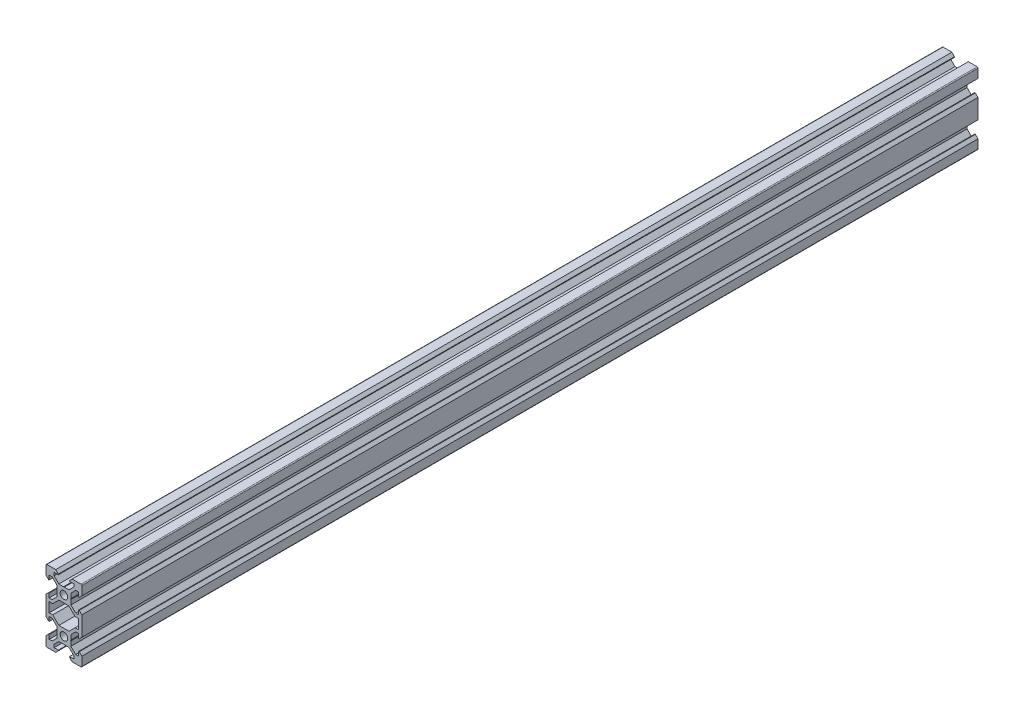
SolidWorks part; units mm, degrees
ref_plane "Front Plane" through (0, 0, 0) normal (0, 0, 1) x (1, 0, 0)
ref_plane "Top Plane" through (0, 0, 0) normal (0, 1, 0) x (1, 0, 0)
ref_plane "Right Plane" through (0, 0, 0) normal (1, 0, 0) x (0, 0, -1)
sketch "Sketch2" plane through (0, 0, 0) normal (0, 0, 1) x (1, 0, 0)
  line L106 (-6.1325, -2.3442) -> (-2.7325, -5.7442)
  line L107 (-8.0932, -2.3442) -> (-6.1325, -2.3442)
  line L108 (-8.0932, -2.3442) -> (-8.0932, 3.0558)
  line L109 (-8.0932, 3.0558) -> (-6.1325, 3.0558)
  line L110 (-6.1325, 3.0558) -> (-2.7325, 6.4558)
  line L111 (-2.7325, 6.4558) -> (2.9461, 6.4558)
  line L112 (6.3461, 3.0558) -> (2.9461, 6.4558)
  line L113 (8.3068, 3.0558) -> (6.3461, 3.0558)
  line L114 (8.3068, -2.3442) -> (8.3068, 3.0558)
  line L115 (8.3068, -2.3442) -> (6.3461, -2.3442)
  line L116 (6.3461, -2.3442) -> (2.9461, -5.7442)
  line L117 (-2.7325, -5.7442) -> (2.9461, -5.7442)
  line L118 (4.0068, 10.1458) -> (3.7968, 10.3558)
  line L119 (3.7968, 10.3558) -> (4.0068, 10.5658)
  line L120 (4.0068, 10.5658) -> (4.0068, 13.1951)
  line L121 (4.0068, 13.1951) -> (6.6675, 15.8558)
  line L122 (6.6675, 15.8558) -> (8.3068, 15.8558)
  line L123 (8.3068, 15.8558) -> (8.3068, 13.4808)
  line L124 (8.3068, 13.4808) -> (8.6518, 13.4808)
  line L125 (8.6518, 13.4808) -> (10.1068, 14.9358)
  line L126 (10.1068, 14.9358) -> (10.1068, 19.8558)
  line L127 (9.6068, 20.3558) -> (4.6868, 20.3558)
  line L128 (4.6868, 20.3558) -> (3.2318, 18.9008)
  line L129 (3.2318, 18.9008) -> (3.2318, 18.5558)
  line L130 (3.2318, 18.5558) -> (5.6068, 18.5558)
  line L131 (5.6068, 18.5558) -> (5.6068, 16.9165)
  line L132 (5.6068, 16.9165) -> (2.9461, 14.2558)
  line L133 (2.9461, 14.2558) -> (0.3168, 14.2558)
  line L134 (0.3168, 14.2558) -> (0.1068, 14.0458)
  line L135 (0.1068, 14.0458) -> (-0.1032, 14.2558)
  line L136 (-0.1032, 14.2558) -> (-2.7325, 14.2558)
  line L137 (-2.7325, 14.2558) -> (-5.3932, 16.9165)
  line L138 (-5.3932, 16.9165) -> (-5.3932, 18.5558)
  line L139 (-5.3932, 18.5558) -> (-3.0182, 18.5558)
  line L140 (-3.0182, 18.5558) -> (-3.0182, 18.9008)
  line L141 (-3.0182, 18.9008) -> (-4.4732, 20.3558)
  line L142 (-4.4732, 20.3558) -> (-9.3932, 20.3558)
  line L143 (-9.8932, 19.8558) -> (-9.8932, 14.9358)
  line L144 (-9.8932, 14.9358) -> (-8.4382, 13.4808)
  line L145 (-8.4382, 13.4808) -> (-8.0932, 13.4808)
  line L146 (-8.0932, 13.4808) -> (-8.0932, 15.8558)
  line L147 (-8.0932, 15.8558) -> (-6.4539, 15.8558)
  line L148 (-6.4539, 15.8558) -> (-3.7932, 13.1951)
  line L149 (-3.7932, 13.1951) -> (-3.7932, 10.5658)
  line L150 (-3.7932, 10.5658) -> (-3.5832, 10.3558)
  line L151 (-3.5832, 10.3558) -> (-3.7932, 10.1458)
  line L152 (-3.7932, 10.1458) -> (-3.7932, 7.5165)
  line L153 (-3.7932, 7.5165) -> (-6.4539, 4.8558)
  line L154 (-6.4539, 4.8558) -> (-8.0932, 4.8558)
  line L155 (-8.0932, 4.8558) -> (-8.0932, 7.2308)
  line L156 (-8.0932, 7.2308) -> (-8.4382, 7.2308)
  line L157 (-8.4382, 7.2308) -> (-9.8932, 5.7758)
  line L158 (-9.8932, 5.7758) -> (-9.8932, -5.0642)
  line L159 (-9.8932, -5.0642) -> (-8.4382, -6.5192)
  line L160 (-8.4382, -6.5192) -> (-8.0932, -6.5192)
  line L161 (-8.0932, -6.5192) -> (-8.0932, -4.1442)
  line L162 (-8.0932, -4.1442) -> (-6.4539, -4.1442)
  line L163 (-6.4539, -4.1442) -> (-3.7932, -6.8049)
  line L164 (-3.7932, -6.8049) -> (-3.7932, -9.4342)
  line L165 (-3.7932, -9.4342) -> (-3.5832, -9.6442)
  line L166 (-3.5832, -9.6442) -> (-3.7932, -9.8542)
  line L167 (-3.7932, -9.8542) -> (-3.7932, -12.4835)
  line L168 (-3.7932, -12.4835) -> (-6.4539, -15.1442)
  line L169 (-6.4539, -15.1442) -> (-8.0932, -15.1442)
  line L170 (-8.0932, -15.1442) -> (-8.0932, -12.7692)
  line L171 (-8.0932, -12.7692) -> (-8.4382, -12.7692)
  line L172 (-8.4382, -12.7692) -> (-9.8932, -14.2242)
  line L173 (-9.8932, -14.2242) -> (-9.8932, -19.1442)
  line L174 (-9.3932, -19.6442) -> (-4.4732, -19.6442)
  line L175 (-4.4732, -19.6442) -> (-3.0182, -18.1892)
  line L176 (-3.0182, -18.1892) -> (-3.0182, -17.8442)
  line L177 (-3.0182, -17.8442) -> (-5.3932, -17.8442)
  line L178 (-5.3932, -17.8442) -> (-5.3932, -16.2049)
  line L179 (-5.3932, -16.2049) -> (-2.7325, -13.5442)
  line L180 (-2.7325, -13.5442) -> (-0.1032, -13.5442)
  line L181 (-0.1032, -13.5442) -> (0.1068, -13.3342)
  line L182 (0.1068, -13.3342) -> (0.3168, -13.5442)
  line L183 (0.3168, -13.5442) -> (2.9461, -13.5442)
  line L184 (2.9461, -13.5442) -> (5.6068, -16.2049)
  line L185 (5.6068, -16.2049) -> (5.6068, -17.8442)
  line L186 (5.6068, -17.8442) -> (3.2318, -17.8442)
  line L187 (3.2318, -17.8442) -> (3.2318, -18.1892)
  line L188 (3.2318, -18.1892) -> (4.6868, -19.6442)
  line L189 (4.6868, -19.6442) -> (9.6068, -19.6442)
  line L190 (10.1068, -19.1442) -> (10.1068, -14.2242)
  line L191 (10.1068, -14.2242) -> (8.6518, -12.7692)
  line L192 (8.6518, -12.7692) -> (8.3068, -12.7692)
  line L193 (8.3068, -12.7692) -> (8.3068, -15.1442)
  line L194 (8.3068, -15.1442) -> (6.6675, -15.1442)
  line L195 (6.6675, -15.1442) -> (4.0068, -12.4835)
  line L196 (4.0068, -12.4835) -> (4.0068, -9.8542)
  line L197 (4.0068, -9.8542) -> (3.7968, -9.6442)
  line L198 (3.7968, -9.6442) -> (4.0068, -9.4342)
  line L199 (4.0068, -9.4342) -> (4.0068, -6.8049)
  line L200 (4.0068, -6.8049) -> (6.6675, -4.1442)
  line L201 (6.6675, -4.1442) -> (8.3068, -4.1442)
  line L202 (8.3068, -4.1442) -> (8.3068, -6.5192)
  line L203 (8.3068, -6.5192) -> (8.6518, -6.5192)
  line L204 (8.6518, -6.5192) -> (10.1068, -5.0642)
  line L205 (10.1068, -5.0642) -> (10.1068, 5.7758)
  line L206 (10.1068, 5.7758) -> (8.6518, 7.2308)
  line L207 (8.6518, 7.2308) -> (8.3068, 7.2308)
  line L208 (8.3068, 7.2308) -> (8.3068, 4.8558)
  line L209 (8.3068, 4.8558) -> (6.6675, 4.8558)
  line L210 (6.6675, 4.8558) -> (4.0068, 7.5165)
  line L211 (4.0068, 7.5165) -> (4.0068, 10.1458)
  circle A4 centre (0.1068, -9.6442) radius 2.1
  circle A5 centre (0.1068, 10.3558) radius 2.1
  arc A6 (10.1068, 19.8558) -> (9.6068, 20.3558) centre (9.6068, 19.8558) ccw
  arc A7 (-9.3932, 20.3558) -> (-9.8932, 19.8558) centre (-9.3932, 19.8558) ccw
  arc A8 (-9.8932, -19.1442) -> (-9.3932, -19.6442) centre (-9.3932, -19.1442) ccw
  arc A9 (9.6068, -19.6442) -> (10.1068, -19.1442) centre (9.6068, -19.1442) ccw
extrude "Boss-Extrude1" add sketch "Sketch2" along normal blind 500
